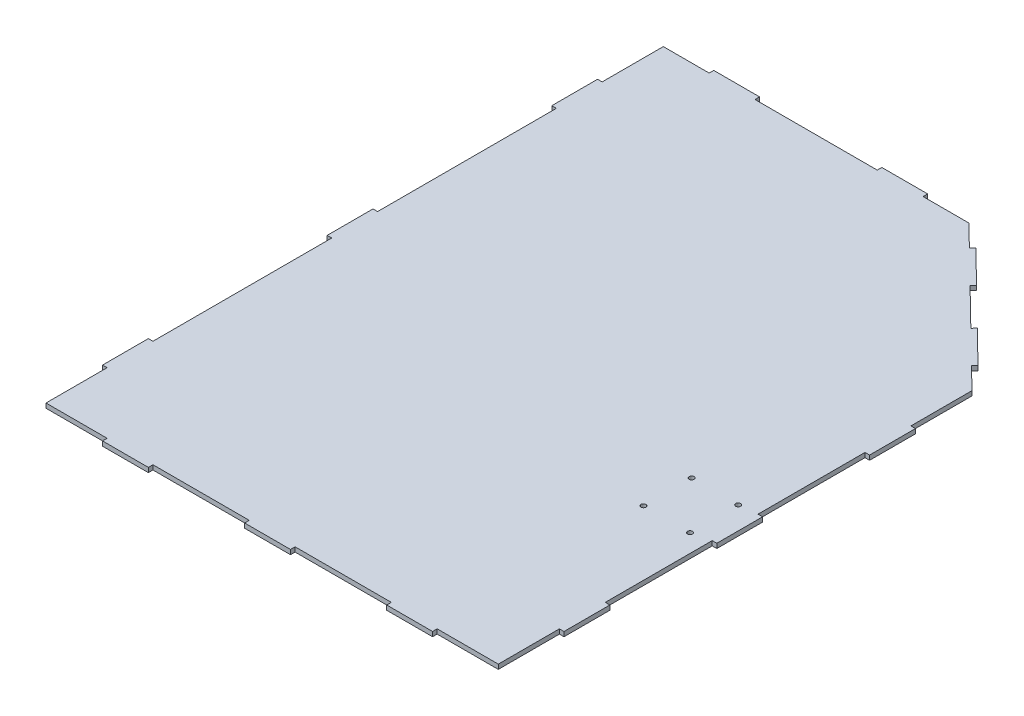
SolidWorks part; units mm, degrees
material "ABS"
ref_plane "Front Plane" through (0, 0, 0) normal (0, 0, 1) x (1, 0, 0)
ref_plane "Top Plane" through (0, 0, 0) normal (0, 1, 0) x (1, 0, 0)
ref_plane "Right Plane" through (0, 0, 0) normal (1, 0, 0) x (0, 0, -1)
sketch "Sketch1" plane through (0, 0, 0) normal (0, 1, 0) x (1, 0, 0)
  line L0 (0, 0) -> (0, 40)
  line L6 (200, 404) -> (214.2902, 390.0075)
  line L7 (296, 310) -> (296, 270)
  line L8 (296, 0) -> (256, 0)
  line L37 (200, 404) -> (170, 404)
  line L51 (40, 0) -> (40, -3)
  line L52 (40, -3) -> (70, -3)
  line L53 (70, 0) -> (70, -3)
  line L55 (133, 0) -> (133, -3)
  line L56 (133, -3) -> (163, -3)
  line L57 (163, 0) -> (163, -3)
  line L59 (226, 0) -> (226, -3)
  line L60 (226, -3) -> (256, -3)
  line L61 (256, 0) -> (256, -3)
  line L62 (214.2902, 390.0075) -> (216.3891, 392.151)
  line L63 (0, 70) -> (-3, 70)
  line L65 (0, 40) -> (-3, 40)
  line L66 (-3, 70) -> (-3, 40)
  line L67 (0, 217) -> (-3, 217)
  line L69 (0, 187) -> (-3, 187)
  line L70 (-3, 217) -> (-3, 187)
  line L71 (0, 364) -> (-3, 364)
  line L73 (0, 334) -> (-3, 334)
  line L74 (-3, 364) -> (-3, 334)
  line L76 (30, 404) -> (30, 407)
  line L77 (30, 407) -> (60, 407)
  line L78 (60, 404) -> (60, 407)
  line L80 (140, 404) -> (140, 407)
  line L81 (140, 407) -> (170, 407)
  line L82 (170, 404) -> (170, 407)
  line L83 (296, 270) -> (299, 270)
  line L86 (299, 270) -> (299, 240)
  line L87 (296, 170) -> (299, 170)
  line L89 (296, 140) -> (299, 140)
  line L90 (299, 170) -> (299, 140)
  line L93 (296, 40) -> (299, 40)
  line L94 (299, 70) -> (299, 40)
  line L95 (216.3891, 392.151) -> (237.8244, 371.1623)
  line L96 (237.8244, 371.1623) -> (235.7255, 369.0188)
  line L97 (260.2745, 344.9812) -> (262.3734, 347.1248)
  line L98 (262.3734, 347.1248) -> (283.8087, 326.136)
  line L99 (283.8087, 326.136) -> (281.7098, 323.9925)
  line L100 (299, 70) -> (296, 70)
  line L101 (299, 240) -> (296, 240)
  line L102 (235.7255, 369.0188) -> (260.2745, 344.9812)
  line L103 (281.7098, 323.9925) -> (296, 310)
  line L104 (296, 240) -> (296, 170)
  line L105 (296, 140) -> (296, 70)
  line L106 (296, 40) -> (296, 0)
  line L107 (226, 0) -> (163, 0)
  line L108 (133, 0) -> (70, 0)
  line L109 (40, 0) -> (0, 0)
  line L110 (0, 70) -> (0, 187)
  line L111 (0, 217) -> (0, 334)
  line L112 (0, 364) -> (0, 404)
  line L113 (30, 404) -> (0, 404)
  line L114 (140, 404) -> (60, 404)
  circle A0 centre (253.75, 168.75) radius 1.6
  circle A1 centre (284.25, 168.75) radius 1.6
  circle A2 centre (284.25, 137.25) radius 1.6
  circle A3 centre (253.75, 137.25) radius 1.6
  dimension "D43" = 3.2
  dimension "D1" = 296
  dimension "D2" = 404
  dimension "D3" = 310
  dimension "D4" = 3
  dimension "D5" = 3
  dimension "D6" = 30
  dimension "D7" = 30
  dimension "D8" = 30
  dimension "D9" = 30
  dimension "D10" = 3
  dimension "D11" = 30
  dimension "D12" = 20
  dimension "D13" = 30
  dimension "D14" = 3
  dimension "D15" = 20
  dimension "D16" = 30
  dimension "D17" = 3
  dimension "D18" = 40
  dimension "D19" = 30
  dimension "D20" = 3
  dimension "D21" = 70
  dimension "D22" = 30
  dimension "D23" = 3
  dimension "D24" = 40
  dimension "D25" = 30
  dimension "D26" = 3
  dimension "D27" = 30
  dimension "D28" = 3
  dimension "D29" = 30
  dimension "D30" = 3
  dimension "D31" = 40
  dimension "D32" = 40
  dimension "D33" = 63
  dimension "D34" = 30
  dimension "D35" = 3
  dimension "D36" = 40
  dimension "D37" = 30
  dimension "D38" = 3
  dimension "D39" = 40
  dimension "D40" = 30
  dimension "D41" = 3
  dimension "D42" = 117
  dimension "D44" = 30.5
  dimension "D45" = 31.5
  dimension "D46" = 11.75
  dimension "D47" = 140.25
extrude "Boss-Extrude1" add sketch "Sketch1" along normal blind 3
